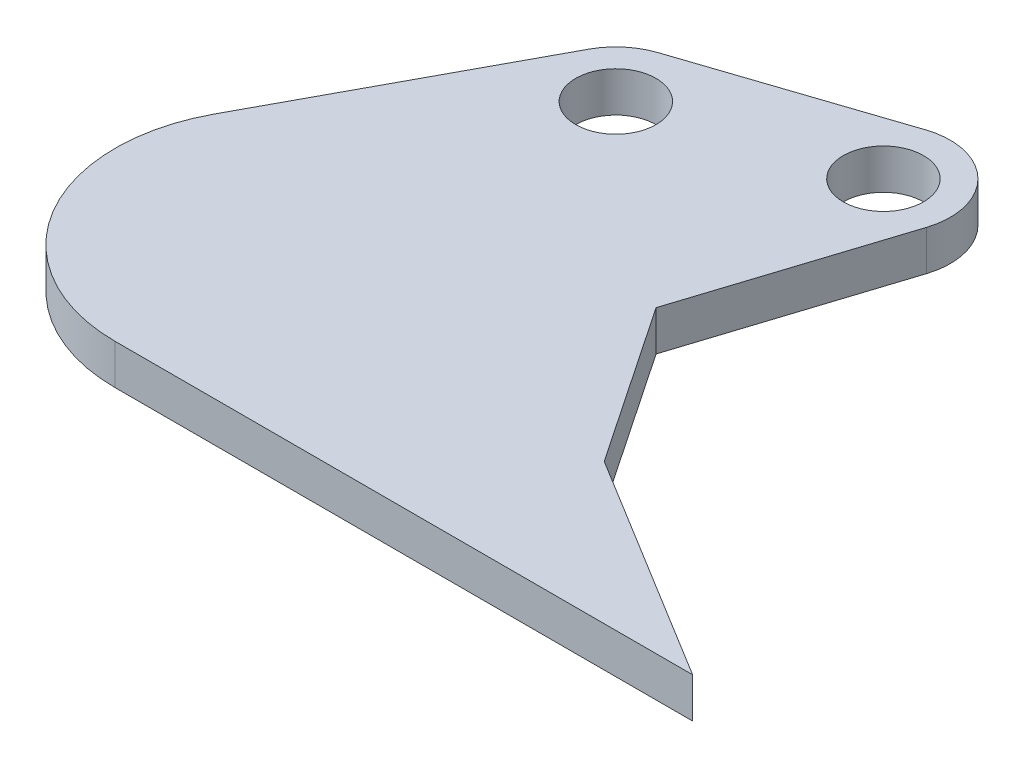
SolidWorks part; units mm, degrees
ref_plane "前视基准面" through (0, 0, 0) normal (0, 0, 1) x (1, 0, 0)
ref_plane "上视基准面" through (0, 0, 0) normal (0, 1, 0) x (1, 0, 0)
ref_plane "右视基准面" through (0, 0, 0) normal (1, 0, 0) x (0, 0, -1)
other "Configuration Table"
sketch "草图2" plane through (0, 0, 0) normal (0, 1, 0) x (1, 0, 0)
  line L14 (-0.1499, -16.8436) -> (14.0508, 27.4456)
  line L15 (-7.451, 19.5673) -> (-37.1147, -35.5261)
  line L16 (-18.1879, -39.241) -> (113.4651, -39.241)
  line L17 (-16.5811, -0.2566) -> (-1.5811, 4.7434)
  line L18 (-0.1499, -16.8436) -> (7.8637, -28.7334)
  line L19 (7.8637, -28.7334) -> (24.9806, -39.241)
  circle A14 centre (0, 0) radius 3
  circle A15 centre (0, 0) radius 5
  circle A16 centre (-15, -5) radius 3
  circle A17 centre (-15, -5) radius 5
  circle A18 centre (-18.1879, -26.741) radius 12.5
  point P5 (0, 0)
  point P8 (-20.422, -36.6085)
  point P19 (-18.1879, -26.741)
  point P20 (7.8637, -28.7334)
  dimension "D1" = 6
  dimension "D2" = 2
  dimension "D3" = 5
  dimension "D5" = 25
  dimension "D4" = 15
extrude "凸台-拉伸1" add sketch "草图2" along normal blind 3 contours A18 L16 L19 L18 L14 A15 L17 A17 L15 | A18 | A17 A16 | A15 A14
